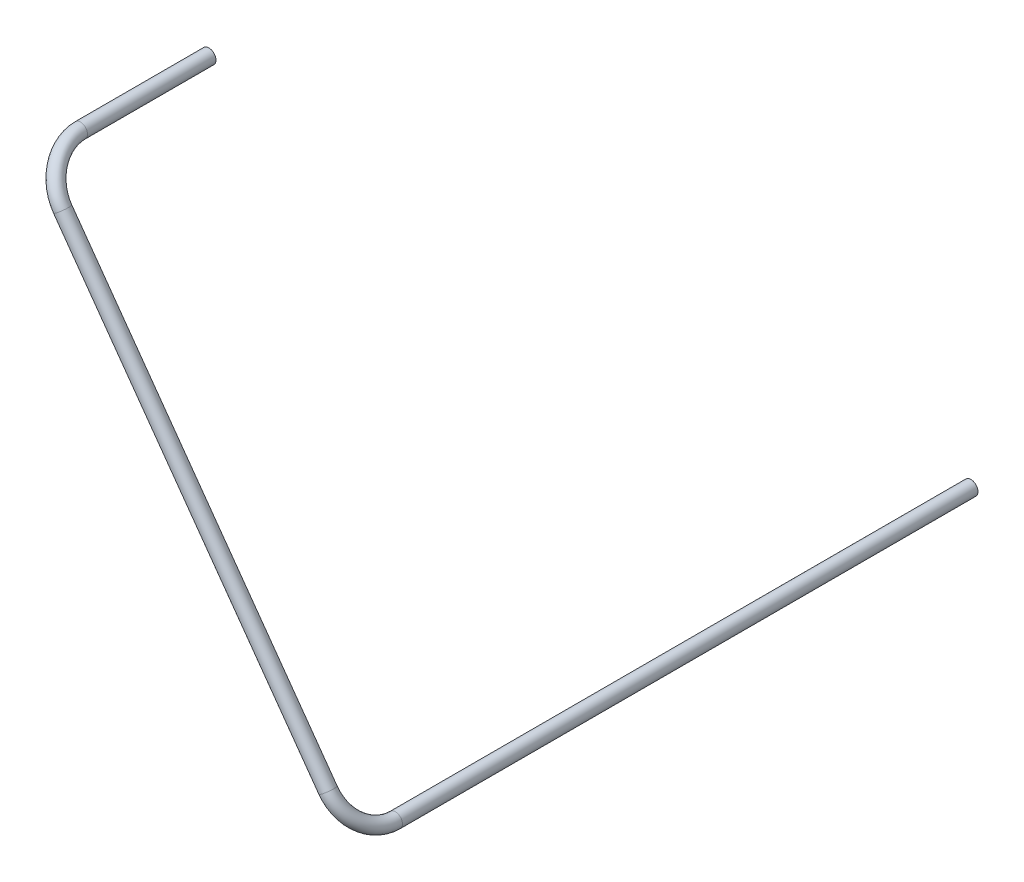
SolidWorks part; units mm, degrees
ref_plane "Front" through (0, 0, 0) normal (0, 0, 1) x (1, 0, 0)
ref_plane "Top" through (0, 0, 0) normal (0, 1, 0) x (1, 0, 0)
ref_plane "Side" through (0, 0, 0) normal (1, 0, 0) x (0, 0, -1)
sketch "PipeSketch" plane through (0, 0, 0) normal (0, 0, 1) x (1, 0, 0)
  circle A0 centre (0, 0) radius 6.35
  circle A1 centre (0, 0) radius 5.1054 construction
  dimension "OuterDiameter" = 12.7
  dimension "InnerDiameter" = 10.2108
sketch "FilterSketch" plane through (0, 0, 0) normal (0, 0, 1) x (1, 0, 0)
  circle A0 centre (0, 0) radius 6.35 construction
  dimension "NominalDiameter" = 12.7
sketch3d "3DSketch1"
  line L0 (0, 0, 0) -> (0, 0, 115.0029) construction
  line L1 (22.182, -30.9769, 153.1029) -> (259.8289, -362.8487, 153.1029) construction
  line L2 (282.0109, -393.8256, -400.3473) -> (282.0109, -393.8256, 115.0029) construction
  line L3 (0, 0, 0) -> (0, 0, 115.0029)
  line L4 (22.182, -30.9769, 153.1029) -> (259.8289, -362.8487, 153.1029)
  line L5 (282.0109, -393.8256, -400.3473) -> (282.0109, -393.8256, 115.0029)
  arc A0 (0, 0, 115.0029) -> (22.182, -30.9769, 153.1029) centre (22.182, -30.9769, 115.0029) ccw construction
  arc A1 (282.0109, -393.8256, 115.0029) -> (259.8289, -362.8487, 153.1029) centre (259.8289, -362.8487, 115.0029) ccw construction
  arc A2 (0, 0, 115.0029) -> (22.182, -30.9769, 153.1029) centre (22.182, -30.9769, 115.0029) ccw
  arc A3 (282.0109, -393.8256, 115.0029) -> (259.8289, -362.8487, 153.1029) centre (259.8289, -362.8487, 115.0029) ccw
  point P4 (53.1589, -8.795, 115.0029)
  point P6 (53.1589, -8.795, 115.0029)
  point P7 (228.852, -385.0307, 115.0029)
  point P12 (228.852, -385.0307, 115.0029)
sweep "ThinSweep" add profiles "PipeSketch" path "3DSketch1" parameters "WallThickness"=1.2446
ref_plane "Plane1" through (0, 0, 0) normal (0, 0, 1) x (1, 0, 0)
